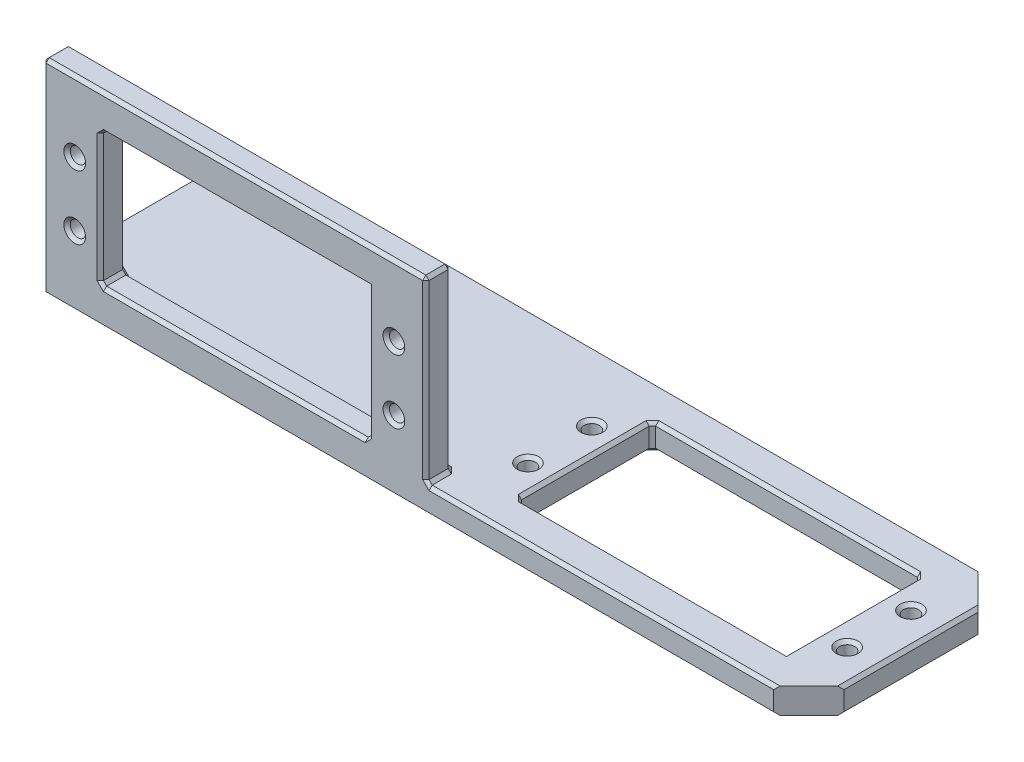
SolidWorks part; units mm, degrees
material "ABS"
ref_plane "Front Plane" through (0, 0, 0) normal (0, 0, 1) x (1, 0, 0)
ref_plane "Top Plane" through (0, 0, 0) normal (0, 1, 0) x (1, 0, 0)
ref_plane "Right Plane" through (0, 0, 0) normal (1, 0, 0) x (0, 0, -1)
sketch "Sketch2" plane through (0, 0, 0) normal (0, 1, 0) x (1, 0, 0)
  line L1 (-60, 16) -> (60, 16)
  line L2 (-60, 16) -> (-60, -16)
  line L3 (-60, -16) -> (60, -16)
  line L4 (60, 16) -> (60, -16)
  line L5 (-60, 16) -> (60, -16) construction
  line L6 (-60, -16) -> (60, 16) construction
  point P0 (0, 0)
  dimension "D1" = 120
  dimension "D2" = 32
extrude "Boss-Extrude1" add sketch "Sketch2" along normal blind 4
sketch "Sketch3" plane through (0, 4, 0) normal (0, 1, 0) x (1, 0, 0)
  line L1 (9, 10.5) -> (51, 10.5)
  line L2 (9, 10.5) -> (9, -10.5)
  line L3 (9, -10.5) -> (51, -10.5)
  line L4 (51, 10.5) -> (51, -10.5)
  line L5 (9, 10.5) -> (51, -10.5) construction
  line L6 (9, -10.5) -> (51, 10.5) construction
  circle A0 centre (55, 5) radius 1.2
  circle A1 centre (55, -5) radius 1.2
  circle A2 centre (5, 5) radius 1.2
  circle A3 centre (5, -5) radius 1.2
  point P0 (30, 0)
  dimension "D4" = 2.4
  dimension "D1" = 42
  dimension "D2" = 21
  dimension "D3" = 9
  dimension "D5" = 5.5
  dimension "D6" = 4
  dimension "D7" = 5.5
  dimension "D8" = 4
extrude "Cut-Extrude1" cut sketch "Sketch3" against normal blind 4
sketch "Sketch4" plane through (0, 0, 16) normal (0, 0, 1) x (1, 0, 0)
  line L1 (-60, 0) -> (0, 0)
  line L2 (-60, 0) -> (-60, 32)
  line L3 (-60, 32) -> (0, 32)
  line L4 (0, 0) -> (0, 32)
  dimension "D1" = 60
  dimension "D2" = 32
extrude "Boss-Extrude2" add sketch "Sketch4" against normal blind 4
sketch "Sketch5" plane through (0, 0, 16) normal (0, 0, 1) x (1, 0, 0)
  line L0 (-60, 0) -> (60, 0) construction
  line L1 (-51, 26.5) -> (-9, 26.5)
  line L2 (-51, 26.5) -> (-51, 5.5)
  line L3 (-51, 5.5) -> (-9, 5.5)
  line L4 (-9, 26.5) -> (-9, 5.5)
  line L5 (-51, 26.5) -> (-9, 5.5) construction
  line L6 (-51, 5.5) -> (-9, 26.5) construction
  line L7 (0, 4) -> (0, 32) construction
  circle A0 centre (-5, 21) radius 1.2
  circle A1 centre (-5, 11) radius 1.2
  circle A2 centre (-55, 21) radius 1.2
  circle A3 centre (-55, 11) radius 1.2
  point P0 (-30, 16)
  dimension "D5" = 2.4
  dimension "D1" = 42
  dimension "D2" = 21
  dimension "D3" = 5.5
  dimension "D4" = 9
  dimension "D6" = 5.5
  dimension "D7" = 4
  dimension "D8" = 4
  dimension "D9" = 5.5
extrude "Cut-Extrude2" cut sketch "Sketch5" against normal through all
chamfer "Chamfer1" distance 0.5 angle 45 56 edges at (-53.8, 11, 16) (-53.8, 21, 16) (-3.8, 11, 16) (-3.8, 21, 16) (-6.2, 21, 12) (-6.2, 11, 12) (-56.2, 21, 12) (-56.2, 11, 12) (5, 4, 6.2) (5, 0, 6.2) (5, 4, -3.8) (5, 0, -3.8) (55, 4, 6.2) (55, 0, 6.2) (55, 4, -3.8) (55, 0, -3.8) (51, 0, 0) (30, 0, 10.5) (51, 4, 0) (30, 4, -10.5) (9, 4, 0) (30, 4, 10.5) (51, 2, -10.5) (30, 0, -10.5) (9, 2, -10.5) (9, 0, 0) (9, 2, 10.5) (-60, 18, 12) (0, 18, 16) (-30, 32, 16) (0, 18, 12) (0, 32, 14) (-30, 32, 12) (-60, 32, 14) (-30, 4, 12) (0, 4, 14) (60, 0, 0) (-60, 16, 16) (0, 0, 16) (30, 4, 16) (60, 2, 16) (60, 4, 0) (-60, 4, -2) (0, 4, -16) (60, 2, -16) (-30, 26.5, 12) (-9, 16, 12) (-9, 16, 16) (-30, 26.5, 16) (-51, 16, 16) (-30, 5.5, 16) (-51, 26.5, 14) (-51, 5.5, 14) (-9, 5.5, 14) (-51, 16, 12) (-30, 5.5, 12)
chamfer "Chamfer2" distance 0.5 angle 45 4 edges at (51, 2, 10.5) (-60, 1.75, -16) (-0.25, 0, -16) (-60, 0, -0.25)
sketch "Sketch7" plane through (0, 4, 0) normal (0, 1, 0) x (1, 0, 0)
  line L0 (54.5, 16) -> (60, 10.5)
  line L1 (-59.5, 16) -> (59.5, 16) construction
  line L2 (60, 15.5) -> (60, -15.5) construction
  line L3 (54.5, 16) -> (63.3251, 18.3318)
  line L4 (63.3251, 18.3318) -> (60, 10.5)
  line L5 (54.5, -16) -> (60, -10.5)
  line L6 (59.5, -16) -> (0.5, -16) construction
  line L7 (60, -10.5) -> (62.0935, -22.5122)
  line L8 (62.0935, -22.5122) -> (54.5, -16)
  dimension "D1" = 5
  dimension "D2" = 5
  dimension "D3" = 5
  dimension "D4" = 5
extrude "Cut-Extrude3" cut sketch "Sketch7" against normal blind 10
